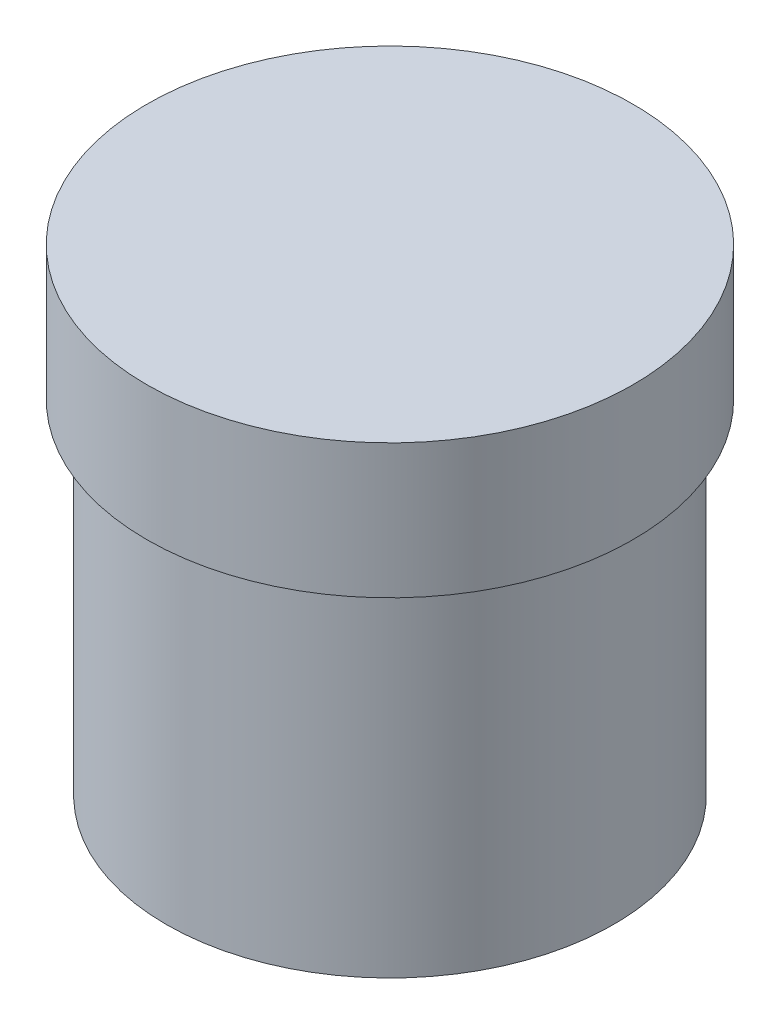
SolidWorks part; units mm, degrees
ref_plane "前视基准面" through (0, 0, 0) normal (0, 0, 1) x (1, 0, 0)
ref_plane "上视基准面" through (0, 0, 0) normal (0, 1, 0) x (1, 0, 0)
ref_plane "右视基准面" through (0, 0, 0) normal (1, 0, 0) x (0, 0, -1)
sketch "草图1" plane through (0, 0, 0) normal (0, 1, 0) x (1, 0, 0)
  circle A0 centre (0, 0) radius 16.3
extrude "上盖" add sketch "草图1" along normal blind 9
sketch "草图2" plane through (0, 0, 0) normal (0, 1, 0) x (1, 0, 0)
  circle A0 centre (0, 0) radius 15
extrude "凸台-拉伸2" add sketch "草图2" against normal blind 23
